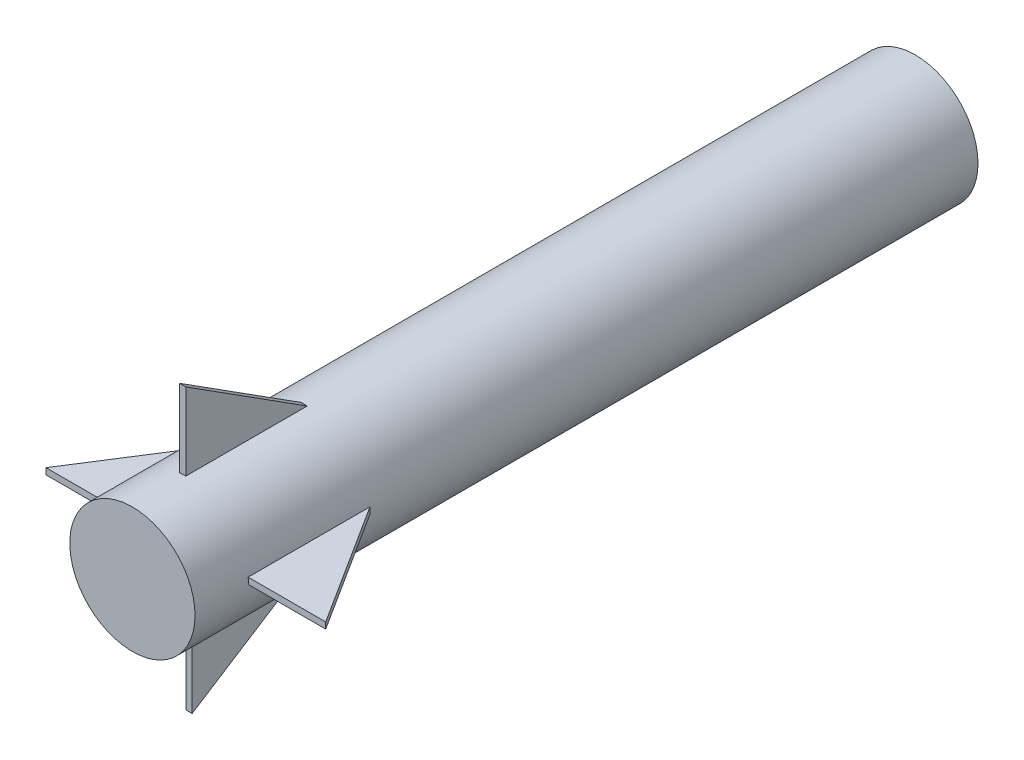
SolidWorks part; units mm, degrees
ref_plane "Płaszczyzna przednia" through (0, 0, 0) normal (0, 0, 1) x (1, 0, 0)
ref_plane "Płaszczyzna górna" through (0, 0, 0) normal (0, 1, 0) x (1, 0, 0)
ref_plane "Płaszczyzna prawa" through (0, 0, 0) normal (1, 0, 0) x (0, 0, -1)
sketch "Szkic1" plane through (0, 0, 0) normal (0, 0, 1) x (1, 0, 0)
  circle A0 centre (0, 0) radius 80
  dimension "D1" = 160
extrude "Dodanie-wyciągnięcie1" add sketch "Szkic1" along normal blind 1000
sketch "Szkic5" plane through (0, 0, 0) normal (0, 1, 0) x (1, 0, 0)
  line L0 (73.6162, -766.7379) -> (178.6162, -931.7379)
  line L1 (178.6162, -931.7379) -> (73.6162, -931.7379)
  line L2 (73.6162, -766.7379) -> (73.6162, -931.7379)
  dimension "D1" = 165
  dimension "D2" = 105
extrude "Dodanie-wyciągnięcie2" add sketch "Szkic5" along normal blind 8
pattern_circular "Szyk kołowy1" count 4 over 360 about axis through (0, 0, 0) along (0, 0, 1) of "Dodanie-wyciągnięcie2"
